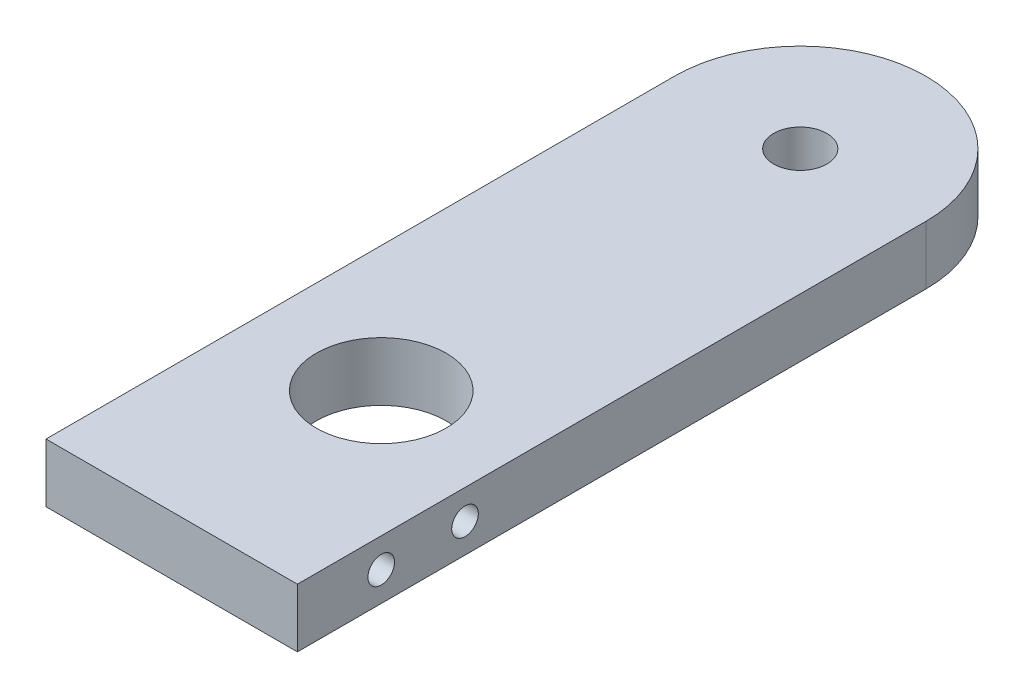
SolidWorks part; units mm, degrees
ref_plane "Front Plane" through (0, 0, 0) normal (0, 0, 1) x (1, 0, 0)
ref_plane "Top Plane" through (0, 0, 0) normal (0, 1, 0) x (1, 0, 0)
ref_plane "Right Plane" through (0, 0, 0) normal (1, 0, 0) x (0, 0, -1)
ref_plane "Plane1" through (0, 7, 0) normal (0, 1, 0) x (1, 0, 0)
sketch "Sketch1" plane through (0, 7, 0) normal (0, 1, 0) x (1, 0, 0)
  line L0 (-125.8012, -29.648) -> (-125.8012, 45.352)
  line L1 (-155.8012, 45.352) -> (-155.8012, -29.648)
  line L2 (-155.8012, -29.648) -> (-125.8012, -29.648)
  arc A0 (-125.8012, 45.352) -> (-155.8012, 45.352) centre (-140.8012, 45.352) ccw
  dimension "D1" = 15
  dimension "D2" = 75
extrude "Boss-Extrude1" add sketch "Sketch1" against normal blind 7
hole_wizard "1/8 (0.125) Diameter Hole1" positions "Sketch3" profile "Sketch2" hole size "1/8" standard "ANSI Inch"
sketch "Sketch3" plane through (-125.8012, 0, 0) normal (1, 0, 0) x (0, 0, -1)
  line L0 (-29.648, 0) -> (-29.648, 7) construction
  point P0 (-19.648, 3.5)
  point P1 (-9.648, 3.5)
  dimension "D1" = 10
  dimension "D2" = 10
sketch "Sketch2" plane through (-125.8012, 3.5, 19.648) normal (0, 1, 0) x (0, 0, -1)
  line L0 (0, 0) -> (0, 4.064)
  line L1 (0, 4.064) -> (1.5875, 4.064)
  line L2 (1.5875, 4.064) -> (1.5875, 0)
  line L5 (1.5875, 0) -> (0, 0)
  line L10 (0, 4.064) -> (-1.5875, 4.064) construction
  line L11 (0, -6.35) -> (0, 107.95) construction
  dimension "Hole Dia." = 3.175
  dimension "Hole Depth" = 4.064
  dimension "Drill Angle" = 180
hole_wizard "Hole1" positions "Sketch5" profile "Sketch4" legacy
sketch "Sketch5" plane through (0, 0, 0) normal (0, -1, 0) x (-1, 0, 0)
  line L0 (155.8012, -29.648) -> (125.8012, -29.648) construction
  line L1 (125.8012, -29.648) -> (125.8012, 45.352) construction
  point P0 (140.8012, -4.648)
  dimension "D1" = 25
  dimension "D2" = 15
sketch "Sketch4" plane through (-140.8012, 0, 4.648) normal (1, 0, 0) x (0, 0, -1)
  line L0 (0, 0) -> (0, 7)
  line L1 (0, 7) -> (7.75, 7)
  line L2 (7.75, 7) -> (7.75, 0)
  line L3 (7.75, 0) -> (0, 0)
  line L4 (0, 110) -> (0, -10) construction
  dimension "Diameter" = 15.5
  dimension "Depth" = 7
hole_wizard "1/4 (0.25) Diameter Hole1" positions "Sketch7" profile "Sketch6" hole size "1/4" standard "ANSI Inch"
sketch "Sketch7" plane through (0, 0, 0) normal (0, -1, 0) x (-1, 0, 0)
  point P0 (140.8012, 45.352)
sketch "Sketch6" plane through (-140.8012, 0, -45.352) normal (1, 0, 0) x (0, 0, -1)
  line L0 (0, 0) -> (0, 7)
  line L1 (0, 7) -> (3.175, 7)
  line L2 (3.175, 7) -> (3.175, 0)
  line L5 (3.175, 0) -> (0, 0)
  line L11 (0, -6.35) -> (0, 107.95) construction
  dimension "Thru Hole Dia." = 6.35
  dimension "Thru Hole Depth" = 7
